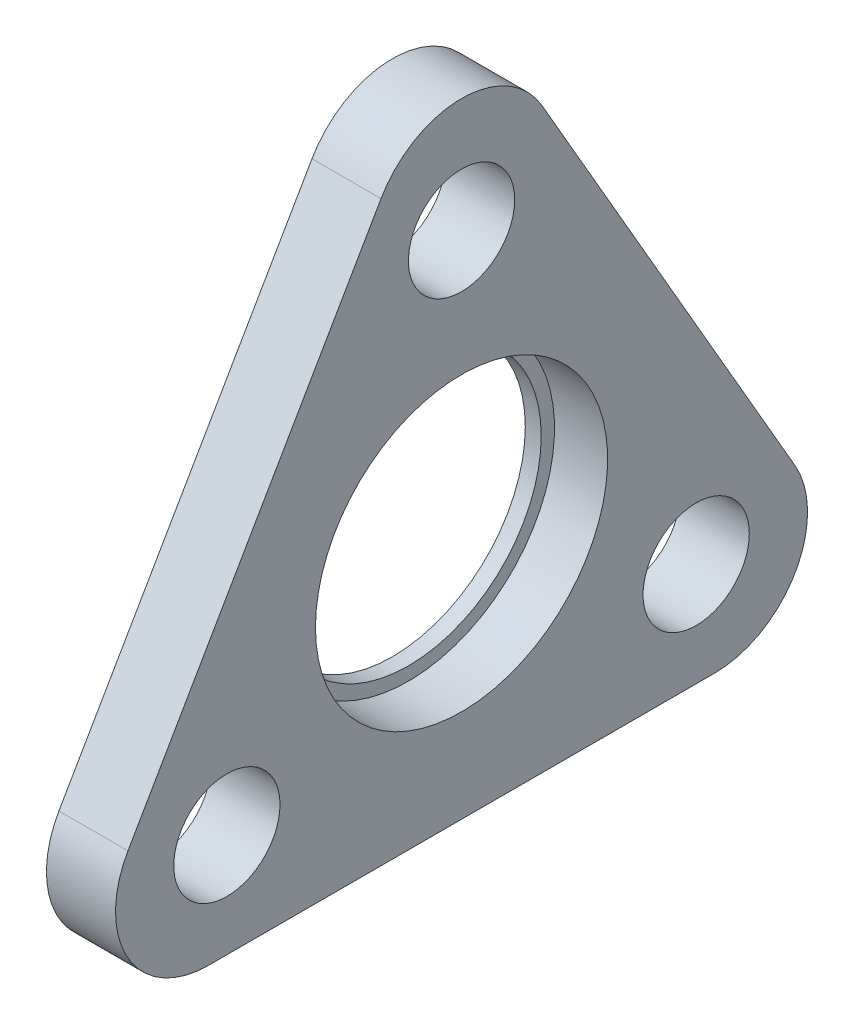
SolidWorks part; units mm, degrees
ref_plane "前视基准面" through (0, 0, 0) normal (0, 0, 1) x (1, 0, 0)
ref_plane "上视基准面" through (0, 0, 0) normal (0, 1, 0) x (1, 0, 0)
ref_plane "右视基准面" through (0, 0, 0) normal (1, 0, 0) x (0, 0, -1)
other "Configuration Table"
sketch "草图1" plane through (0, 0, 0) normal (1, 0, 0) x (0, 0, -1)
  line L0 (0, 0) -> (0, 10.2) construction
  line L1 (0, 0) -> (8.8335, -5.1) construction
  line L2 (0, 0) -> (-8.8335, -5.1) construction
  line L3 (0, 0) -> (0, 18)
  line L4 (0, 0) -> (15.5885, -9)
  line L5 (0, 0) -> (-15.5885, -9)
  line L6 (0, 18) -> (-15.5885, -9)
  line L7 (-15.5885, -9) -> (15.5885, -9)
  line L8 (15.5885, -9) -> (0, 18)
  circle A0 centre (0, 10.2) radius 3.55 construction
  circle A1 centre (8.8335, -5.1) radius 3.55 construction
  circle A2 centre (-8.8335, -5.1) radius 3.55 construction
  circle A3 centre (0, 10.2) radius 2
  circle A4 centre (8.8335, -5.1) radius 2
  circle A5 centre (-8.8335, -5.1) radius 2
  point P7 (0, 0)
  point P19 (0, 0)
  dimension "D3" = 7.1
  dimension "D4" = 7.1
  dimension "D5" = 7.1
  dimension "D11" = 4
  dimension "D1" = 10.2
  dimension "D6" = 120
  dimension "D7" = 120
  dimension "D8" = 18
  dimension "D9" = 18
  dimension "D10" = 18
  dimension "D2" = 3
  dimension "D12" = 3
extrude "凸台-拉伸2" add sketch "草图1" along normal blind 2.6 contours A4 L4 L8 L3 A3 | A5 L5 L3 A3 L6 | A5 L5 L7 L4 A4
fillet "圆角1" radius 3.5 3 edges at (1.3, -9, 15.5885) (1.3, -9, -15.5885) (1.3, 18, 0)
sketch "草图4" plane through (0, 0, 0) normal (-1, 0, 0) x (0, 0, 1)
  circle A0 centre (0, 0) radius 5.5
extrude "切除-拉伸1" cut sketch "草图4" against normal through all
sketch "草图6" plane through (0, 0, 0) normal (-1, 0, 0) x (0, 0, 1)
  circle A0 centre (0, 0) radius 5
  circle A1 centre (0, 0) radius 5.5
extrude "凸台-拉伸4" add sketch "草图6" against normal blind 0.6 separate body
